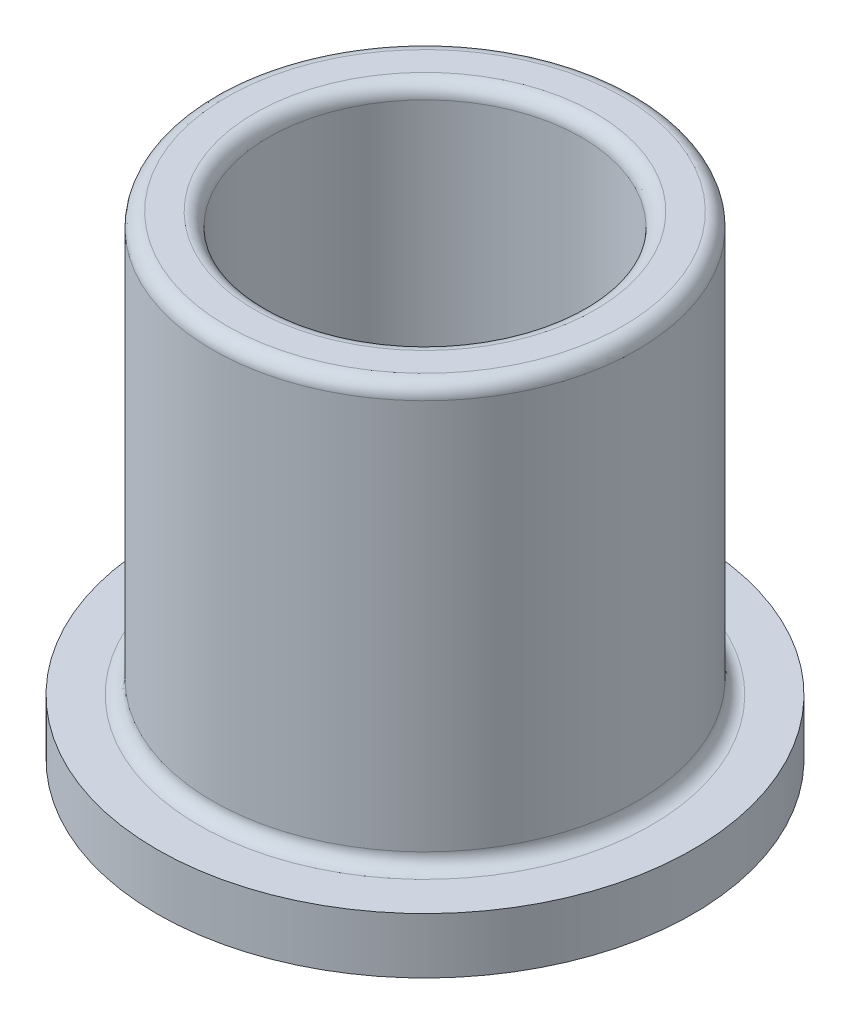
SolidWorks part; units mm, degrees
ref_plane "Front Plane" through (0, 0, 0) normal (0, 0, 1) x (1, 0, 0)
ref_plane "Top Plane" through (0, 0, 0) normal (0, 1, 0) x (1, 0, 0)
ref_plane "Right Plane" through (0, 0, 0) normal (1, 0, 0) x (0, 0, -1)
sketch "Sketch1" plane through (0, 0, 0) normal (0, 0, 1) x (1, 0, 0)
  line L0 (35.5863, 107.95) -> (48.2863, 107.95)
  line L1 (35.5863, 107.95) -> (35.5863, 0)
  line L2 (48.2863, 12.7) -> (48.2863, 107.95)
  line L3 (0, 107.95) -> (0, 0) construction
  line L4 (35.5863, 0) -> (60.9863, 0)
  line L5 (60.9863, 0) -> (60.9863, 12.7)
  line L6 (48.2863, 12.7) -> (60.9863, 12.7)
  dimension "D1" = 12.7
revolve "Revolve1" add sketch "Sketch1" angle 360 about L3
fillet "Fillet1" radius 3.175 3 edges at (0, 12.7, 48.2863) (0, 107.95, 48.2863) (0, 107.95, 35.5863)
ref_plane "Plane1" through (0, 107.95, 0) normal (0, 1, 0) x (-1, 0, 0)
sketch "Sketch2" plane through (0, 107.95, 0) normal (0, 1, 0) x (-1, 0, 0)
  line L0 (0, 0) -> (-45.1113, 0) construction
  circle A0 centre (0, 0) radius 45.1113 construction
